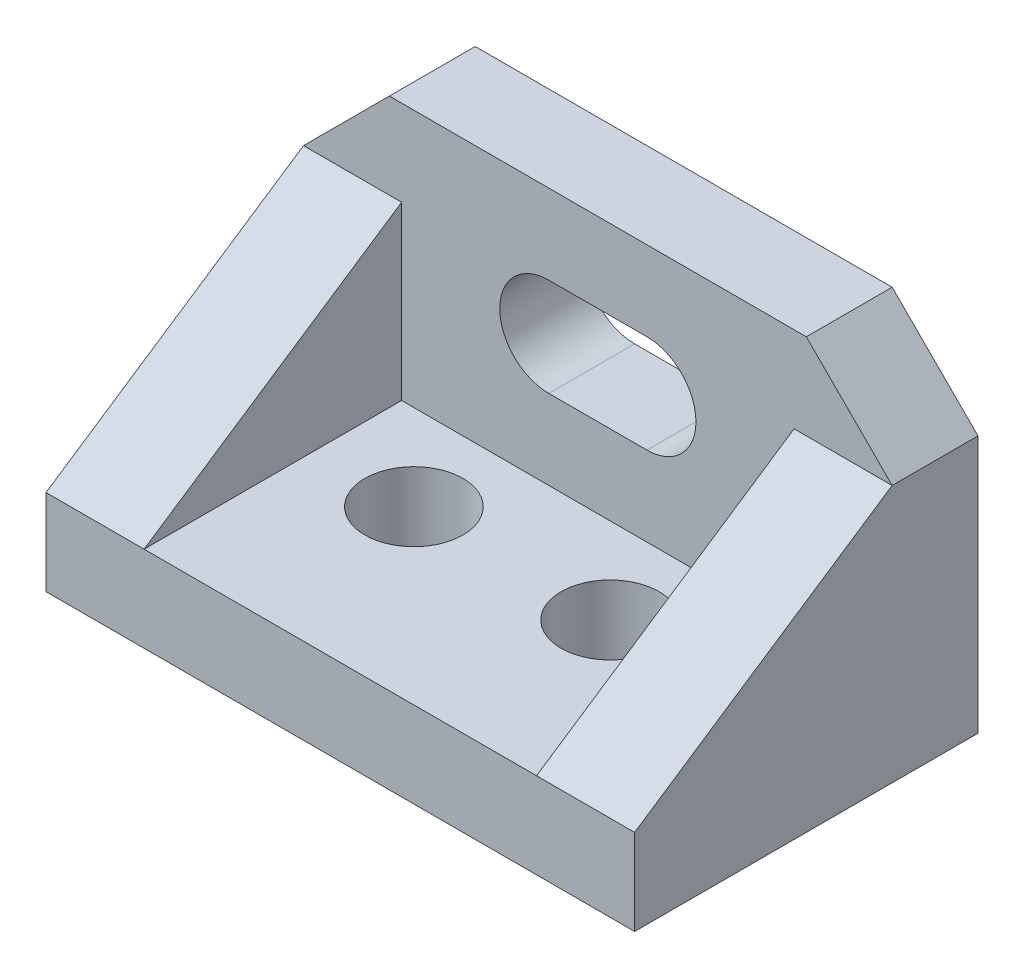
SolidWorks part; units mm, degrees
ref_plane "Front Plane" through (0, 0, 0) normal (0, 0, 1) x (1, 0, 0)
ref_plane "Top Plane" through (0, 0, 0) normal (0, 1, 0) x (1, 0, 0)
ref_plane "Right Plane" through (0, 0, 0) normal (1, 0, 0) x (0, 0, -1)
sketch "Sketch1" plane through (0, 0, 0) normal (0, 1, 0) x (1, 0, 0)
  line L0 (0, 0) -> (0, 88.9)
  line L2 (152.4, 88.9) -> (152.4, 0)
  line L3 (152.4, 0) -> (0, 0)
  line L4 (0, 88.9) -> (25.4, 88.9)
  line L5 (25.4, 88.9) -> (127, 88.9)
  line L6 (127, 88.9) -> (152.4, 88.9)
  dimension "D1" = 152.4
  dimension "D2" = 25.4
  dimension "D3" = 25.4
  dimension "D4" = 88.9
extrude "Boss-Extrude2" add sketch "Sketch1" along normal blind 22.225
sketch "Sketch4" plane through (0, 22.225, 0) normal (0, 1, 0) x (1, 0, 0)
  line L0 (0, 0) -> (25.4, 0)
  line L1 (0, 0) -> (152.4, 0) construction
  line L2 (25.4, 0) -> (25.4, 66.675)
  line L3 (25.4, 66.675) -> (0, 66.675)
  line L4 (0, 88.9) -> (0, 0) construction
  line L5 (0, 66.675) -> (0, 0)
  line L6 (152.4, 0) -> (152.4, 66.675)
  line L7 (152.4, 0) -> (152.4, 88.9) construction
  line L8 (152.4, 66.675) -> (127, 66.675)
  line L9 (127, 66.675) -> (127, 0)
  line L10 (127, 0) -> (152.4, 0)
  dimension "D2" = 25.4
  dimension "D1" = 25.4
  dimension "D3" = 66.675
  dimension "D4" = 66.675
extrude "Boss-Extrude5" add sketch "Sketch4" along normal blind 44.45
sketch "Sketch5" plane through (152.4, 0, 0) normal (1, 0, 0) x (0, 0, -1)
  line L0 (66.675, 66.675) -> (0, 22.225)
  line L1 (0, 22.225) -> (0, 66.675)
  line L2 (0, 66.675) -> (66.675, 66.675)
extrude "Cut-Extrude1" cut sketch "Sketch5" against normal through all
sketch "Sketch6" plane through (0, 22.225, 0) normal (0, 1, 0) x (1, 0, 0)
  line L0 (152.4, 88.9) -> (0, 88.9)
  line L1 (0, 88.9) -> (0, 66.675)
  line L2 (0, 66.675) -> (152.4, 66.675)
  line L3 (152.4, 66.675) -> (152.4, 88.9)
extrude "Boss-Extrude6" add sketch "Sketch6" along normal blind 66.675
sketch "Sketch7" plane through (0, 0, -66.675) normal (0, 0, 1) x (1, 0, 0)
  line L0 (152.4, 66.675) -> (152.4, 88.9)
  line L2 (0, 88.9) -> (152.4, 88.9) construction
  line L5 (152.4, 66.675) -> (127, 66.675) construction
  line L6 (130.175, 88.9) -> (152.4, 66.675)
  line L7 (130.175, 88.9) -> (152.4, 88.9)
  dimension "D1" = 45
extrude "Cut-Extrude2" cut sketch "Sketch7" against normal through all
sketch "Sketch8" plane through (0, 0, -66.675) normal (0, 0, 1) x (1, 0, 0)
  line L0 (0, 88.9) -> (22.225, 88.9)
  line L1 (0, 88.9) -> (130.175, 88.9) construction
  line L2 (22.225, 88.9) -> (0, 66.675)
  line L3 (0, 66.675) -> (0, 88.9)
  line L4 (25.4, 66.675) -> (0, 66.675) construction
  dimension "D1" = 45
extrude "Cut-Extrude3" cut sketch "Sketch8" against normal through all
sketch "Sketch9" plane through (0, 22.225, 0) normal (0, 1, 0) x (1, 0, 0)
  circle A0 centre (50.8, 44.45) radius 12.7
  circle A1 centre (101.6, 44.45) radius 12.7
  dimension "D5" = 25.4
  dimension "D6" = 25.4
  dimension "D2" = 50.8
  dimension "D1" = 50.8
extrude "Cut-Extrude4" cut sketch "Sketch9" against normal through all
sketch "Sketch12" plane through (0, 0, -66.675) normal (0, 0, 1) x (1, 0, 0)
  line L0 (63.5, 55.5625) -> (88.9, 55.5625) construction
  line L2 (63.5, 55.5625) -> (88.9, 55.5625)
  line L3 (63.5, 68.2625) -> (88.9, 68.2625)
  line L4 (63.5, 42.8625) -> (88.9, 42.8625)
  line L6 (22.225, 88.9) -> (130.175, 88.9) construction
  arc A0 (63.5, 68.2625) -> (63.5, 42.8625) centre (63.5, 55.5625) ccw
  arc A1 (88.9, 42.8625) -> (88.9, 68.2625) centre (88.9, 55.5625) ccw
  point P0 (76.2, 55.5625)
  point P5 (0, 0)
  point P8 (0, 0)
  point P11 (0, 0)
  point P12 (50.8, 55.5625)
  dimension "D1" = 25.4
  dimension "D2" = 63.5
  dimension "D3" = 12.7
  dimension "D4" = 33.3375
extrude "Cut-Extrude5" cut sketch "Sketch12" against normal through all
equation "\"l\"= 6"
equation "\"x\"= ( \"l\" * 2 / 3 ) - .5in"
equation "\"D1@Sketch1\"=\"l\""
equation "\"D2@Sketch1\"=\"l\"/6"
equation "\"D3@Sketch1\"=\"l\"/6"
equation "\"D4@Sketch1\"=\"x\""
equation "\"D1@Boss-Extrude2\"=\"x\"/4"
equation "\"D1@Sketch4\"=\"l\"/6"
equation "\"D2@Sketch4\"=\"l\"/6"
equation "\"D3@Sketch4\"=(\"x\"*3)/4"
equation "\"D4@Sketch4\"=(\"x\"*3)/4"
equation "\"D1@Boss-Extrude5\"=\"x\"/2"
equation "\"D1@Boss-Extrude6\"=(\"x\"*3)/4"
equation "\"D5@Sketch9\"=\"l\"/6"
equation "\"D6@Sketch9\"=\"l\"/6"
equation "\"D2@Sketch9\"=\"l\"/3"
equation "\"D1@Sketch9\"=\"l\"/3"
equation "\"D1@Sketch12\"=\"l\"/6"
equation "\"D2@Sketch12\"=(5*\"l\")/12"
equation "\"D3@Sketch12\"=\"l\"/12"
